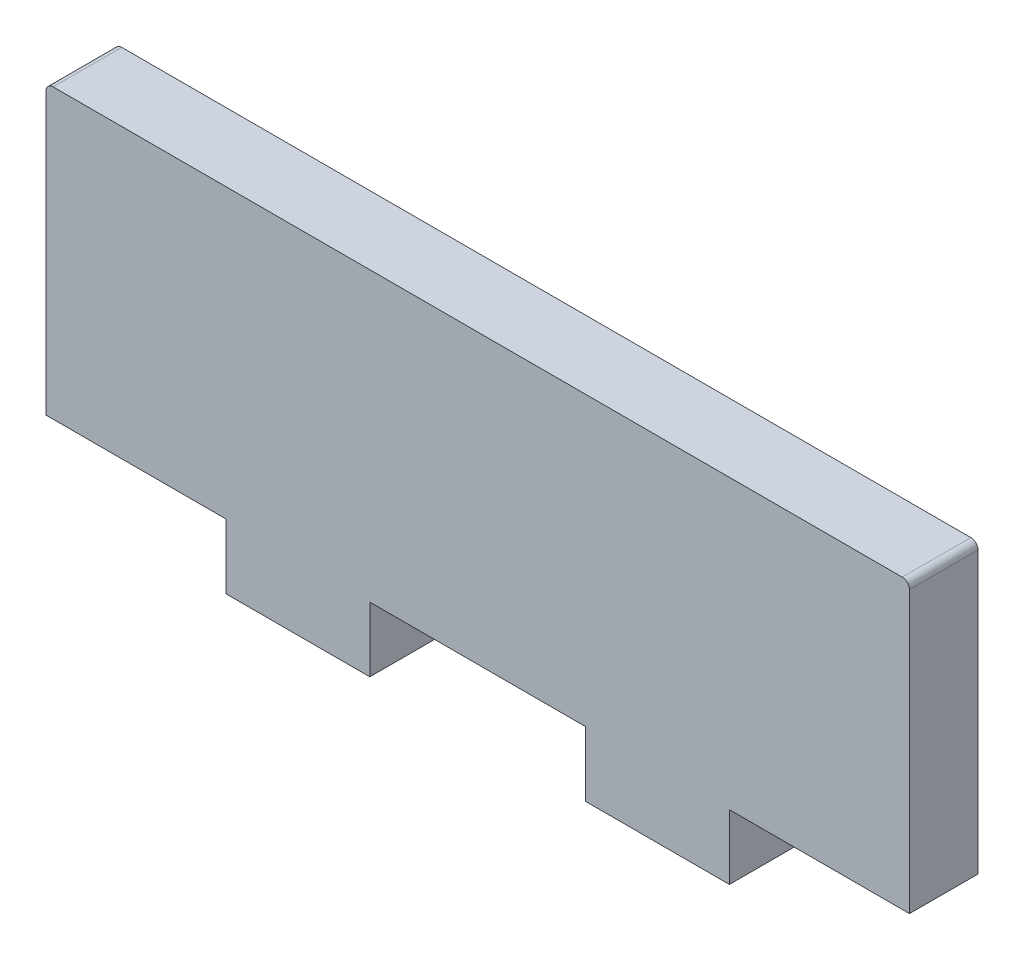
SolidWorks part; units mm, degrees
material "PC High Viscosity"
ref_plane "Front Plane" through (0, 0, 0) normal (0, 0, 1) x (1, 0, 0)
ref_plane "Top Plane" through (0, 0, 0) normal (0, 1, 0) x (1, 0, 0)
ref_plane "Right Plane" through (0, 0, 0) normal (1, 0, 0) x (0, 0, -1)
sketch "Sketch1" plane through (0, 0, 0) normal (0, 0, 1) x (1, 0, 0)
  line L1 (-60, 20) -> (60, 20)
  line L2 (-60, 20) -> (-60, -20)
  line L3 (-60, -20) -> (60, -20)
  line L4 (60, 20) -> (60, -20)
  line L5 (-60, 20) -> (60, -20) construction
  line L6 (-60, -20) -> (60, 20) construction
  line L7 (-34.98, -20) -> (-15, -20)
  line L8 (-34.98, -20) -> (-34.98, -29)
  line L9 (-34.98, -29) -> (-15, -29)
  line L10 (-15, -20) -> (-15, -29)
  line L11 (-34.98, -20) -> (-15, -29) construction
  line L12 (-34.98, -29) -> (-15, -20) construction
  line L13 (15, -20) -> (34.98, -20)
  line L14 (15, -20) -> (15, -29)
  line L15 (15, -29) -> (34.98, -29)
  line L16 (34.98, -20) -> (34.98, -29)
  line L17 (15, -20) -> (34.98, -29) construction
  line L18 (15, -29) -> (34.98, -20) construction
  point P4 (0, 0)
  point P11 (-24.99, -24.5)
  point P15 (24.99, -24.5)
  dimension "D1" = 19.98
  dimension "D2" = 15
  dimension "D3" = 15
  dimension "D4" = 9
  dimension "D5" = 120
  dimension "D6" = 40
extrude "Boss-Extrude1" add sketch "Sketch1" along normal mid plane 9.525 contours L4 L1 L2 L3 | L10 L3 L8 L9 | L16 L3 L14 L15
fillet "Fillet1" radius 1 2 edges at (60, 20, 0) (-60, 20, 0)
equation "\"D1@Sketch1\"=20-\"tol_general_clear\"*2"
equation "\"tol_dia_id_intfc\" = 0.0200mm ' For hole diameters - Interference fit"
equation "\"tol_dia_id_slip\"  = 0.0300mm ' For hole diameters - Slip fit"
equation "\"tol_dia_id_clear\" = 0.0500mm ' For hole diameters - Clearance fit"
equation "\"tol_dia_od_intfc\" = 0.0200mm ' For shaft diameters - Interference fit"
equation "\"tol_dia_od_slip\"  = 0.0300mm ' For shaft diameters - Slip fit"
equation "\"tol_dia_od_clear\" = 0.0500mm ' For shaft diameters - Clearance fit"
equation "\"tol_general_intfc\"= 0.0030mm ' For general parts (Horiz) - Interference fit"
equation "\"tol_general_slip\" = 0.0050mm ' For general parts (Horiz) - Slip fit"
equation "\"tol_general_clear\"= 0.0100mm ' For general parts (Horiz) - Clearance fit"
equation "\"tol_layer_intfc\"  = 0.0030mm ' For all parts (Vert) - Interference fit"
equation "\"tol_layer_slip\"   = 0.0050mm ' For all parts (Vert) - Slip fit"
equation "\"tol_layer_clear\"  = 0.0100mm ' For all parts (Vert) - Clearance fit"
equation "\"tol_corner_rad\"   = 0.100mm ' For corners that fit into other parts"
equation "\"D3@Sketch1\"=\"D2@Sketch1\""
